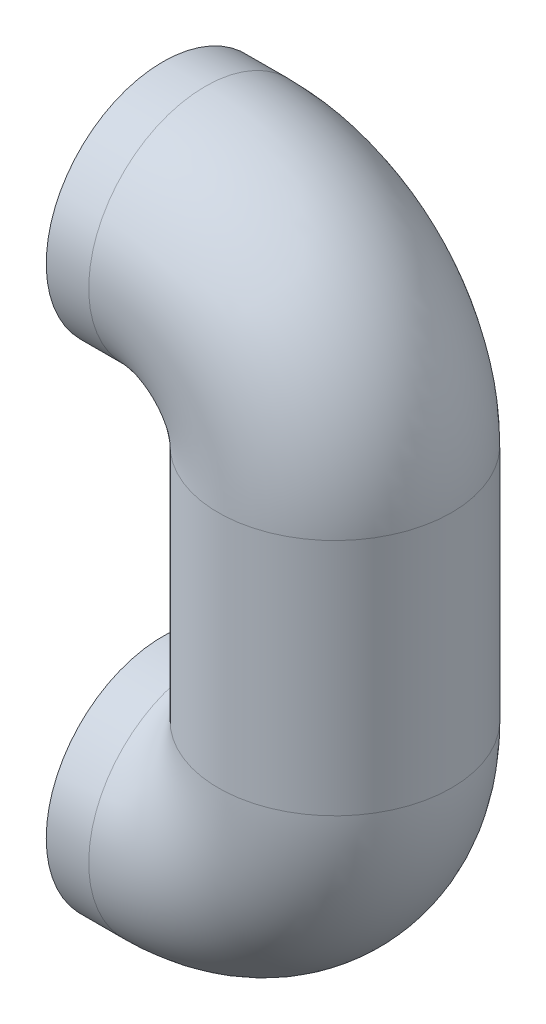
SolidWorks part; units mm, degrees
ref_plane "Front Plane" through (0, 0, 0) normal (0, 0, 1) x (1, 0, 0)
ref_plane "Top Plane" through (0, 0, 0) normal (0, 1, 0) x (1, 0, 0)
ref_plane "Right Plane" through (0, 0, 0) normal (1, 0, 0) x (0, 0, -1)
sketch "Sketch1" plane through (0, 0, 0) normal (0, 0, 1) x (1, 0, 0)
  line L0 (0, 0) -> (8.2, 0)
  line L1 (33.2, 25) -> (33.2, 71)
  line L2 (8.2, 96) -> (0, 96)
  arc A0 (33.2, 71) -> (8.2, 96) centre (8.2, 71) ccw
  arc A1 (8.2, 0) -> (33.2, 25) centre (8.2, 25) ccw
  point P7 (33.2, 96)
  point P10 (33.2, 0)
  dimension "D4" = 25
  dimension "D1" = 96
  dimension "D2" = 33.2
  dimension "D3" = 33.2
sketch "Sketch2" plane through (0, 0, 0) normal (1, 0, 0) x (0, 0, -1)
  circle A0 centre (0, 0) radius 22.5
  dimension "D1" = 45
sweep "Sweep1" add profiles "Sketch2" path "Sketch1"
